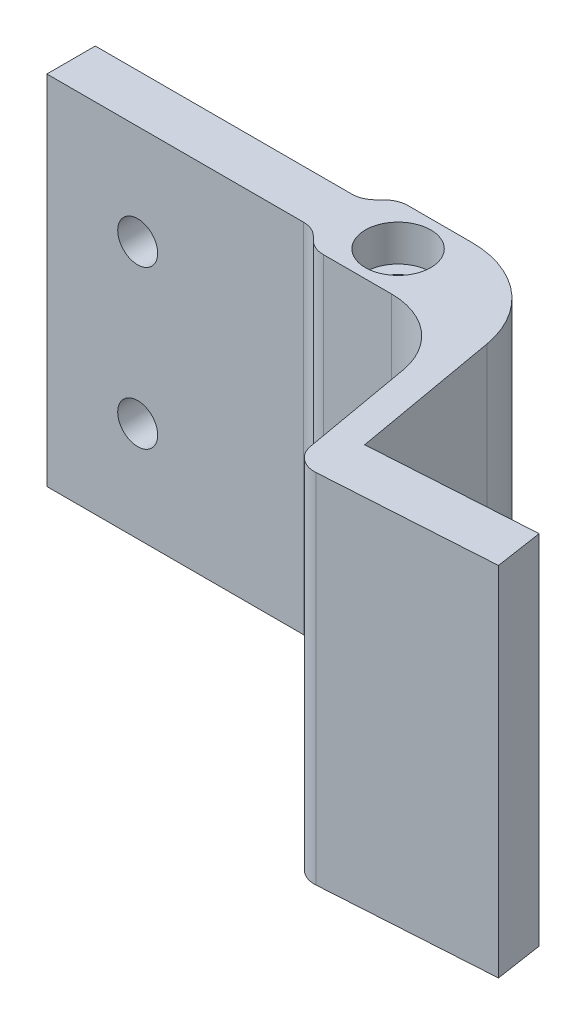
SolidWorks part; units mm, degrees
ref_plane "Ebene vorne" through (0, 0, 0) normal (0, 0, 1) x (1, 0, 0)
ref_plane "Ebene oben" through (0, 0, 0) normal (0, 1, 0) x (1, 0, 0)
ref_plane "Ebene rechts" through (0, 0, 0) normal (1, 0, 0) x (0, 0, -1)
sketch "Sketch1" plane through (0, 0, 0) normal (0, 1, 0) x (1, 0, 0)
  line L0 (0, 4) -> (22, 4)
  line L1 (36.3043, 5.5) -> (39.6358, -13.3938)
  line L2 (39.6358, -13.3938) -> (53.193, -12.5448)
  line L3 (53.193, -12.5448) -> (53.79, -16.5)
  line L4 (53.79, -16.5) -> (37.8212, -17.5)
  line L5 (37.8212, -17.5) -> (35, -1.5)
  line L6 (22, 4) -> (22, -3.8691) construction
  line L7 (0, 0) -> (0, 4)
  line L8 (0, 2) -> (3.9295, 2) construction
  line L9 (22, 4) -> (23.5, 5.5)
  line L10 (23.5, 5.5) -> (30.5, 5.5)
  line L11 (30.5, 5.5) -> (36.3043, 5.5)
  line L12 (22, 0) -> (23.5, -1.5)
  line L13 (23.5, -1.5) -> (35, -1.5)
  line L14 (12.951, -17.5) -> (55.1046, -17.5) construction
  line L15 (27, 5.5) -> (27, 2.7754) construction
  line L18 (22, 0) -> (0, 0)
  circle A0 centre (27, 2) radius 1.65
  point P23 (0, 0)
  dimension "D6" = 3.3
  dimension "D1" = 4
  dimension "D2" = 17.5
  dimension "D3" = 2.5
  dimension "D4" = 100
  dimension "D5" = 8
  dimension "D7" = 35
  dimension "D8" = 16
  dimension "D9" = 45
  dimension "D10" = 1.5
  dimension "D11" = 45
  dimension "D12" = 7
  dimension "D13" = 1
  dimension "D14" = 1.5
  dimension "D15" = 17.5
  dimension "D16" = 4
  dimension "D17" = 95
extrude "Boss-Extrude1" add sketch "Sketch1" along normal blind 29.5
sketch "Sketch2" plane through (0.9903, 0, 15.8139) normal (-0.0625, 0, -0.998) x (-0.998, 0, 0.0625)
  line L0 (-38.7212, 14.75) -> (-52.3049, 14.75) construction
  line L1 (-38.7212, 29.5) -> (-38.7212, 0) construction
  line L2 (-52.3049, 29.5) -> (-52.3049, 0) construction
  circle A0 centre (-44.9712, 14.75) radius 6.25
  dimension "D1" = 12.5
extrude "Magnet Pocket" cut sketch "Sketch2" against normal offset from surface (3.2348 mm away) 0.75 up to face at (45.8056, 14.75, 17)
sketch "Sketch3" plane through (0, 0, -4) normal (0, 0, -1) x (-1, 0, 0)
  line L0 (0, 14.75) -> (-17.3067, 14.75) construction
  line L1 (0, 29.5) -> (0, 0) construction
  line L3 (-7.5, 8.25) -> (-7.5, 21.25) construction
  line L4 (-7.5, 14.75) -> (-8.3801, 14.75) construction
  circle A0 centre (-7.5, 8.25) radius 1.65
  circle A1 centre (-7.5, 21.25) radius 1.65
  dimension "D1" = 3.3
  dimension "D2" = 3.3
  dimension "D3" = 13
  dimension "D4" = 7.5
sketch "Sketch4" plane through (0, 29.5, 0) normal (0, 1, 0) x (1, 0, 0)
  circle A0 centre (27, 2) radius 2.7
  dimension "D1" = 5.4
extrude "Cut-Extrude3" cut sketch "Sketch4" against normal blind 3
sketch "Sketch5" plane through (0, 0, 0) normal (0, -1, 0) x (1, 0, 0)
  circle A0 centre (27, -2) radius 2.7
  circle A1 centre (27, -2) radius 2.7 construction
extrude "Cut-Extrude4" cut sketch "Sketch5" against normal blind 3
extrude "Paddle Mount M3" cut sketch "Sketch3" against normal up to surface (4 mm away) up to face at (11, 14.75, 0)
fillet "Fillet4" radius 8 1 edges at (36.3043, 14.75, -5.5)
fillet "Fillet5" radius 6 1 edges at (35, 14.75, 1.5)
sketch "Sketch7" plane through (1.2394, 0, 19.7908) normal (0.0625, 0, 0.998) x (0.998, 0, -0.0625)
  line L0 (44.6535, 29.5) -> (44.6535, 0) construction
  line L1 (36.6535, 29.5) -> (52.6535, 29.5) construction
  line L2 (36.6535, 0) -> (52.6535, 0) construction
  line L3 (44.6535, 14.75) -> (52.6535, 14.75) construction
  line L5 (52.6535, 29.5) -> (52.6535, 0) construction
  circle A0 centre (44.6535, 4.75) radius 1.65
  circle A1 centre (44.6535, 24.75) radius 1.65
  dimension "D3" = 3.3
  dimension "D1" = 10
  dimension "D2" = 10
extrude "M3 Pinch Screws" [suppressed] cut sketch "Sketch7" against normal blind 10
sketch "Sketch8" [suppressed] plane through (0, 0, 23.2621) normal (0, 0, 1) x (1, 0, 0)
  circle A0 centre (46.6754, 4.5) radius 3
  circle A1 centre (46.6754, 24.5) radius 3
  dimension "D1" = 6
extrude "M3 Screw Head" [suppressed] cut sketch "Sketch8" against normal blind 10 draft 45
fillet "Fillet6" radius 2 1 edges at (37.8212, 14.75, 17.5)
fillet "Fillet7" radius 2 1 edges at (23.5, 14.75, -5.5)
fillet "Fillet8" radius 2 1 edges at (22, 14.75, -4)
fillet "Fillet9" radius 2 1 edges at (23.5, 14.75, 1.5)
fillet "Fillet10" radius 2 1 edges at (22, 14.75, 0)
